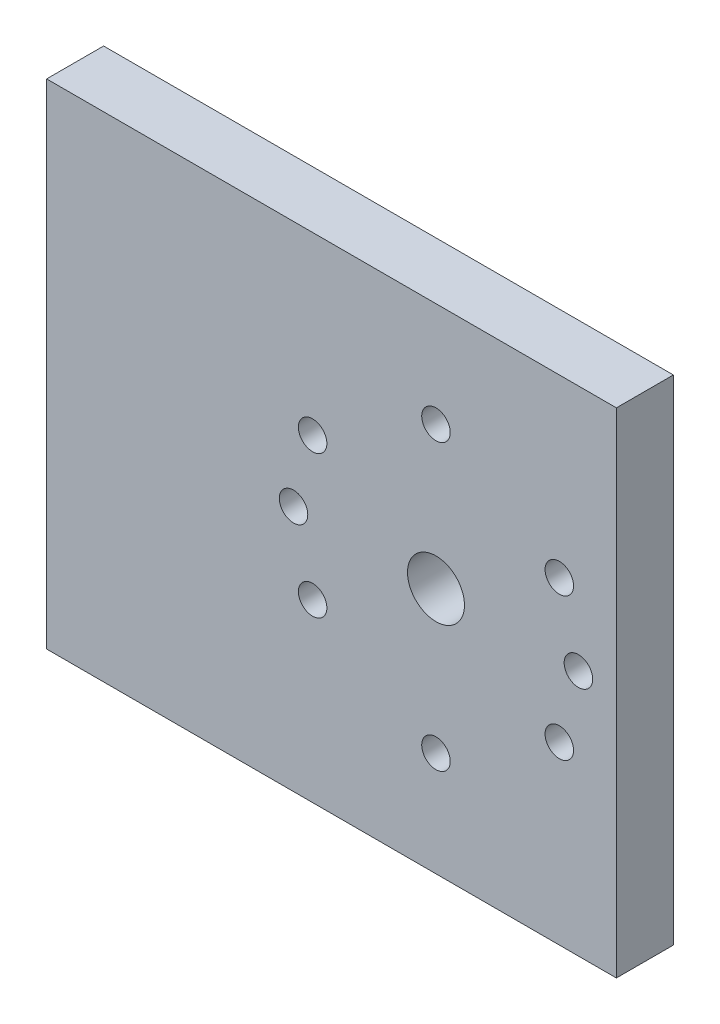
SolidWorks part; units mm, degrees
ref_plane "Alzado" through (0, 0, 0) normal (0, 0, 1) x (1, 0, 0)
ref_plane "Planta" through (0, 0, 0) normal (0, 1, 0) x (1, 0, 0)
ref_plane "Vista lateral" through (0, 0, 0) normal (1, 0, 0) x (0, 0, -1)
sketch "Sketch1" plane through (0, 0, 0) normal (0, 0, 1) x (1, 0, 0)
  line L0 (0, -26) -> (30, -26)
  line L1 (0, 0) -> (30, 0)
  line L2 (0, 0) -> (0, -26)
  line L4 (30, 0) -> (30, -26)
  line L5 (0, 0) -> (30, -26) construction
  line L6 (20.5, -13) -> (30, -13) construction
  circle A0 centre (20.5, -13) radius 7.5 construction
  circle A1 centre (20.5, -5.5) radius 0.75
  circle A2 centre (26.9952, -9.25) radius 0.75
  circle A3 centre (26.9952, -16.75) radius 0.75
  circle A4 centre (20.5, -20.5) radius 0.75
  circle A5 centre (14.0048, -16.75) radius 0.75
  circle A6 centre (14.0048, -9.25) radius 0.75
  circle A7 centre (20.5, -13) radius 1.5
  circle A8 centre (13, -13) radius 0.75
  circle A9 centre (28, -13) radius 0.75
  point P0 (0, 0)
  point P43 (20.5, -13)
  dimension "D7" = 15
  dimension "D8" = 1.5
  dimension "D10" = 3
  dimension "D1" = 30
  dimension "D2" = 26
  dimension "D3" = 9.5
  dimension "D4" = 13
  dimension "D9" = 6
extrude "Boss-Extrude1" add sketch "Sketch1" along normal blind 3
